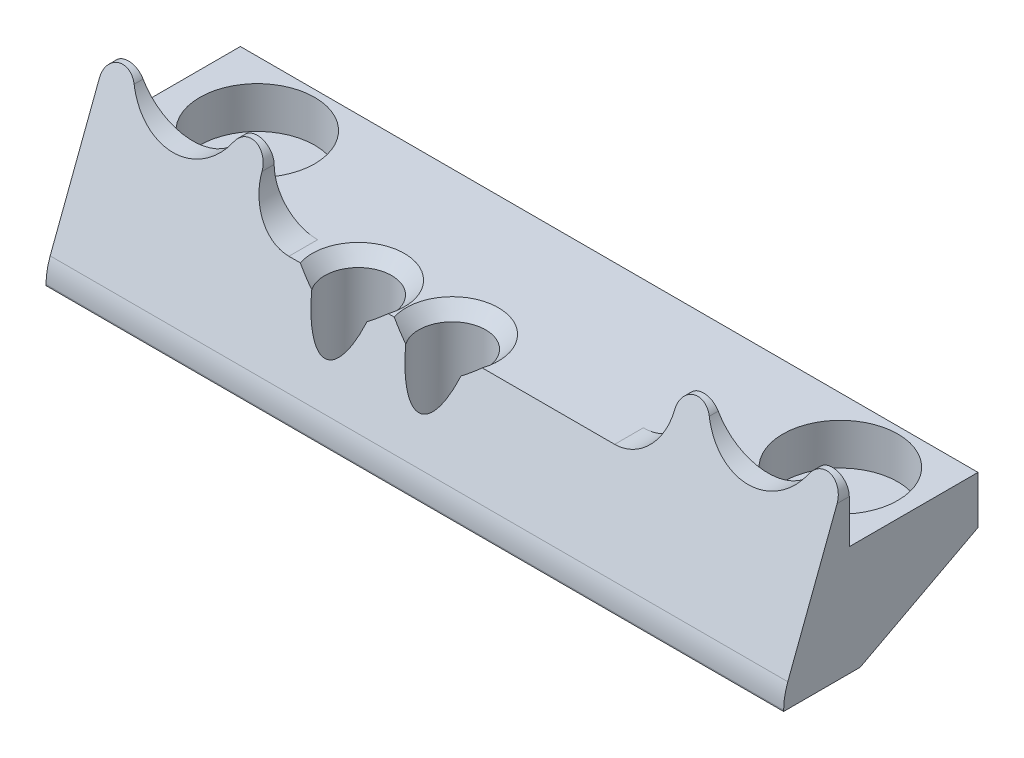
SolidWorks part; units mm, degrees
ref_plane "Front Plane" through (0, 0, 0) normal (0, 0, 1) x (1, 0, 0)
ref_plane "Top Plane" through (0, 0, 0) normal (0, 1, 0) x (1, 0, 0)
ref_plane "Right Plane" through (0, 0, 0) normal (1, 0, 0) x (0, 0, -1)
sketch "Sketch1" plane through (0, 0, 0) normal (0, 1, 0) x (1, 0, 0)
  line L0 (-55.75, -8) -> (60, -8)
  line L1 (-43, -8) -> (-43, 12.4) construction
  line L2 (48.5, -7.3326) -> (48.5, 12.4) construction
  line L3 (-57.25, 2.3) -> (-57.25, 22.5) construction
  line L4 (61.5, 1.1212) -> (61.5, 22.5) construction
  line L5 (-55.75, -8) -> (-55.75, 22.5)
  line L6 (60, -8) -> (60, 22.5)
  line L7 (-55.75, 2.3) -> (-55.75, 22.5) construction
  line L8 (60, 1.1212) -> (60, 22.5) construction
  line L9 (-55.75, 22.5) -> (60, 22.5)
  circle A0 centre (0, 0) radius 2.75
  circle A1 centre (-14.75, 0) radius 2.75
  circle A2 centre (-43, 12.4) radius 8.525 construction
  circle A3 centre (48.5, 12.4) radius 8.525 construction
  circle A4 centre (48.5, 12.4) radius 9.025
  circle A5 centre (-43, 12.4) radius 9.025
  point P7 (60, 21.652)
  point P16 (-57.25, 12.4)
  point P21 (61.5, 11.8106)
  point P28 (48.5, 11.7326)
  dimension "D1" = 5.5
  dimension "D6" = 20.2
  dimension "D12" = 17.05
  dimension "D2" = 14.75
  dimension "D3" = 8
  dimension "D4" = 28.25
  dimension "D5" = 91.5
  dimension "D7" = 10.3
  dimension "D8" = 14.25
  dimension "D9" = 13
  dimension "D10" = 1.5
  dimension "D11" = 1.5
  dimension "D13" = 0.5
extrude "Boss-Extrude1" add sketch "Sketch1" along normal blind 17.25
sketch "Sketch3" plane through (0, 0, 0) normal (0, -1, 0) x (1, 0, 0)
  circle A0 centre (48.5, -12.4) radius 9.025 construction
  circle A1 centre (-43, -12.4) radius 9.025 construction
  circle A2 centre (48.5, -12.4) radius 9.025
  circle A3 centre (-43, -12.4) radius 9.025
extrude "Boss-Extrude2" add sketch "Sketch3" against normal offset from surface (10.75 mm away) 6.5 up to face at (2.125, 17.25, -7.25)
sketch "Sketch4" plane through (0, 17.25, 0) normal (0, 1, 0) x (1, 0, 0)
  circle A0 centre (0, 0) radius 2.75 construction
  circle A1 centre (-14.75, 0) radius 2.75 construction
  circle A4 centre (0, 0) radius 2.75 construction
  circle A5 centre (-14.75, 0) radius 2.75 construction
  circle A6 centre (-14.75, 0) radius 5.25
  circle A7 centre (0, 0) radius 5.25
  dimension "D1" = 2.5
extrude "Cut-Extrude1" cut sketch "Sketch4" against normal offset from surface (14.25 mm away) 3 up to face at (0, 0, 2.75)
sketch "Sketch5" plane through (0, 17.25, 0) normal (0, 1, 0) x (1, 0, 0)
  line L0 (-55.75, -8) -> (60, -8)
  line L1 (-43, -8) -> (-43, 12.4) construction
  line L2 (48.5, -7.3326) -> (48.5, 12.4) construction
  line L3 (-57.25, 2.3) -> (-57.25, 22.5) construction
  line L4 (61.5, 1.1212) -> (61.5, 22.5) construction
  line L5 (-55.75, -8) -> (-55.75, 22.5)
  line L6 (60, -8) -> (60, 22.5)
  line L7 (-55.75, 2.3) -> (-55.75, 22.5) construction
  line L8 (60, 1.1212) -> (60, 22.5) construction
  line L9 (-55.75, 22.5) -> (60, 22.5)
  circle A0 centre (0, 0) radius 2.75
  circle A1 centre (-14.75, 0) radius 2.75
  circle A2 centre (-43, 12.4) radius 8.525 construction
  circle A3 centre (48.5, 12.4) radius 8.525 construction
  circle A4 centre (48.5, 12.4) radius 9.025
  circle A5 centre (-43, 12.4) radius 9.025
  point P7 (35.666, 23.4543)
  point P16 (-57.25, 12.4)
  point P21 (61.5, 11.8106)
  point P28 (24.166, 13.5349)
  point P29 (0, 0)
  dimension "D1" = 5.5
  dimension "D6" = 20.2
  dimension "D12" = 17.05
  dimension "D2" = 14.75
  dimension "D3" = 8
  dimension "D4" = 28.25
  dimension "D5" = 91.5
  dimension "D7" = 10.3
  dimension "D8" = 14.25
  dimension "D9" = 13
  dimension "D10" = 1.5
  dimension "D11" = 1.5
  dimension "D13" = 0.5
ref_plane "Plane1" through (0, 0, -2.3) normal (0, 0, 1) x (1, 0, 0)
ref_point "Point1"
sketch "Sketch8" plane through (60, 0, 0) normal (1, 0, 0) x (0, 0, -1)
  line L0 (-2.2, 17.25) -> (-7.3468, 3.7174)
  line L1 (-8, 17.25) -> (22.5, 17.25) construction
  line L2 (-8, 17.25) -> (-8, 0) construction
  line L3 (-8, 0.1626) -> (-8, 0) construction
  line L4 (-8, 0.1626) -> (-8, 17.25)
  line L5 (-8, 17.25) -> (-2.2, 17.25)
  line L7 (-8, 17.25) -> (22.5, 17.25) construction
  line L8 (22.5, 9.75) -> (4, 0)
  line L9 (22.5, 17.25) -> (22.5, 0) construction
  line L10 (-8, 0) -> (22.5, 0) construction
  line L11 (4, 0) -> (22.5, 0)
  line L12 (22.5, 0) -> (22.5, 9.75)
  line L14 (21.425, 10.75) -> (3.375, 10.75) construction
  line L15 (21.425, 10.75) -> (3.375, 10.75) construction
  arc A0 (-7.3468, 3.7174) -> (-8, 0.1626) centre (2, 0.1626) ccw
  point P11 (-8, 2)
  point P15 (0, 0)
  point P17 (2.3, 17.25)
  point P30 (0, 0)
  point P31 (22.5, 9.5276)
  dimension "D3" = 10
  dimension "D1" = 4.5
  dimension "D2" = 2
  dimension "D4" = 12
  dimension "D5" = 1
extrude "Cut-Extrude2" cut sketch "Sketch8" against normal through all both and the other way through all
ref_plane "Plane3" through (0, 4.5106, 11.8596) normal (0, 0.3555, 0.9347) x (1, 0, 0)
sketch "Sketch7" plane through (0, 0, -2.3) normal (0, 0, 1) x (1, 0, 0)
  line L1 (-55.75, 17.25) -> (-55.75, 24.0654)
  line L2 (-55.75, 17.25) -> (60, 17.25) construction
  line L3 (-50.8159, 25.3875) -> (-46.1177, 17.25) construction
  line L4 (2.125, 0) -> (2.125, 50000) construction
  line L5 (-55.75, 0) -> (60, 0) construction
  line L6 (-43, 20.875) -> (-43, 17.25) construction
  line L7 (-55.75, 17.25) -> (-23.4346, 17.25)
  line L8 (60, 17.25) -> (60, 24.0654)
  line L9 (60, 17.25) -> (27.6846, 17.25)
  line L10 (-55.75, 3.7174) -> (-55.75, 17.25) construction
  arc A0 (-50.3829, 25.6375) -> (-35.6171, 25.6375) centre (-43, 29.9) ccw construction
  arc A1 (-50.8159, 25.3875) -> (-35.1841, 25.3875) centre (-43, 29.9) ccw
  arc A2 (-50.8159, 25.3875) -> (-55.75, 24.0654) centre (-53.1058, 24.0654) ccw
  arc A3 (-35.1841, 25.3875) -> (-30.25, 24.0654) centre (-32.8942, 24.0654) cw
  arc A4 (-30.25, 24.0654) -> (-23.4346, 17.25) centre (-23.4346, 24.0654) ccw
  arc A5 (55.0659, 25.3875) -> (60, 24.0654) centre (57.3558, 24.0654) cw
  arc A6 (55.0659, 25.3875) -> (39.4341, 25.3875) centre (47.25, 29.9) cw
  arc A7 (39.4341, 25.3875) -> (34.5, 24.0654) centre (37.1442, 24.0654) ccw
  arc A8 (34.5, 24.0654) -> (27.6846, 17.25) centre (27.6846, 24.0654) cw
  point P0 (-43, 17.25)
  point P2 (48.5, 17.25)
  point P21 (2.125, 0)
  point P38 (0, 0)
  point P39 (-55.75, 17.25)
  dimension "D1" = 8.525
  dimension "D3" = 12.65
  dimension "D4" = 60
  dimension "D2" = 0.5
extrude "Boss-Extrude4" add sketch "Sketch7" along normal up to surface (1.4051 mm away) contours A7 A8 L9 L8 A5 A6 | A4 L7 L1 A2 A1 A3
chamfer "Chamfer1" distance 2 angle 45 2 edges at (0, 17.25, -5.25) (-14.75, 17.25, -5.25)
